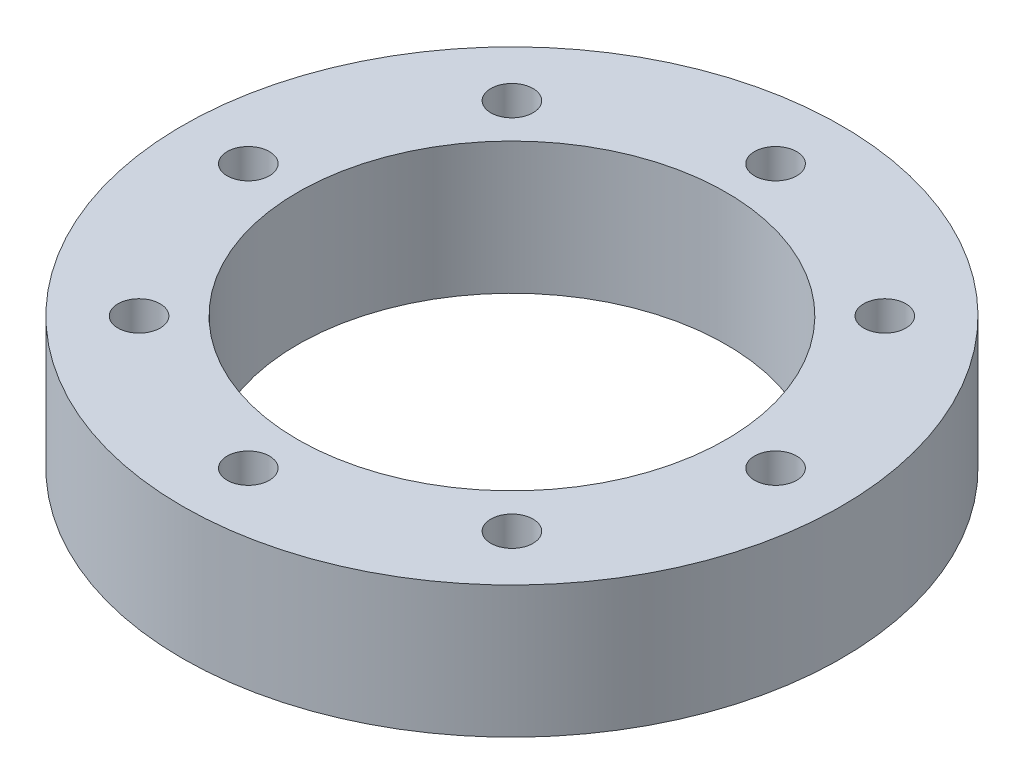
SolidWorks part; units mm, degrees
ref_plane "前视基准面" through (0, 0, 0) normal (0, 0, 1) x (1, 0, 0)
ref_plane "上视基准面" through (0, 0, 0) normal (0, 1, 0) x (1, 0, 0)
ref_plane "右视基准面" through (0, 0, 0) normal (1, 0, 0) x (0, 0, -1)
sketch "草图1" plane through (0, 0, 0) normal (0, 1, 0) x (1, 0, 0)
  circle A0 centre (0, 0) radius 32.5
  circle A1 centre (0, 0) radius 50
  dimension "D1" = 65
  dimension "D2" = 100
extrude "凸台-拉伸1" add sketch "草图1" along normal blind 20
sketch "草图2" plane through (0, 20, 0) normal (0, 1, 0) x (1, 0, 0)
  circle A0 centre (0, 0) radius 40 construction
  circle A1 centre (0, 40) radius 3.2
  circle A2 centre (28.2843, 28.2843) radius 3.2
  circle A3 centre (40, 0) radius 3.2
  circle A4 centre (28.2843, -28.2843) radius 3.2
  circle A5 centre (0, -40) radius 3.2
  circle A6 centre (-28.2843, -28.2843) radius 3.2
  circle A7 centre (-40, 0) radius 3.2
  circle A8 centre (-28.2843, 28.2843) radius 3.2
  point P21 (0, 0)
  dimension "D1" = 80
  dimension "D2" = 6.4
  dimension "D3" = 8
extrude "切除-拉伸1" cut sketch "草图2" against normal blind 20
cosmetic thread "装饰螺纹线1" parameters "D2"=10
cosmetic thread "装饰螺纹线2" parameters "D2"=10
cosmetic thread "装饰螺纹线3" parameters "D2"=10
cosmetic thread "装饰螺纹线4" parameters "D2"=10
cosmetic thread "装饰螺纹线5" parameters "D2"=10
cosmetic thread "装饰螺纹线6" parameters "D2"=10
cosmetic thread "装饰螺纹线7" parameters "D2"=10
cosmetic thread "装饰螺纹线8" parameters "D2"=10
